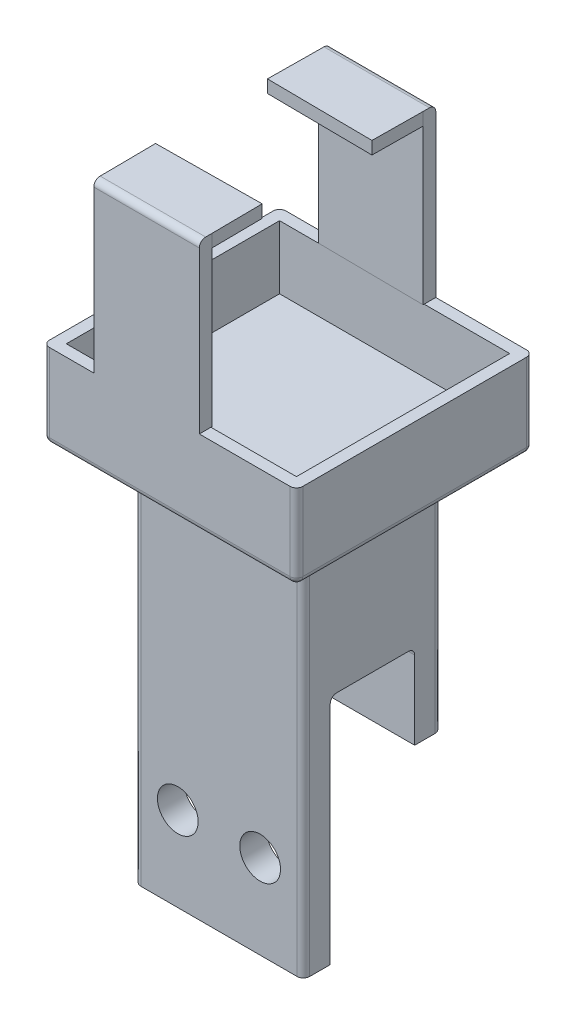
SolidWorks part; units mm, degrees
ref_plane "Front Plane" through (0, 0, 0) normal (0, 0, 1) x (1, 0, 0)
ref_plane "Top Plane" through (0, 0, 0) normal (0, 1, 0) x (1, 0, 0)
ref_plane "Right Plane" through (0, 0, 0) normal (1, 0, 0) x (0, 0, -1)
sketch "Sketch1" plane through (0, 0, 0) normal (1, 0, 0) x (0, 0, -1)
  line L0 (-10, 55) -> (10, 55) construction
  line L1 (-10, 0) -> (-10, 53.5)
  line L2 (-8.5, 55) -> (8.5, 55)
  line L3 (10, 53.5) -> (10, 35)
  line L6 (-16.35, 0) -> (-16.35, 61.35)
  line L7 (-16.35, 61.35) -> (16.35, 61.35)
  line L8 (16.35, 61.35) -> (16.35, 35)
  line L13 (10, -166.8123) -> (-3.9458, 0.265) construction
  line L14 (10, 35) -> (10, -166.8123) construction
  line L15 (16.35, -319.2285) -> (-10.2738, -0.2632) construction
  line L16 (16.35, 35) -> (16.35, -319.2285) construction
  line L17 (10, 35) -> (16.35, 35)
  line L18 (10, 55) -> (10, 35) construction
  line L19 (-10, 0) -> (-10, 55) construction
  line L20 (0, 55) -> (0, -55) construction
  line L21 (-16.35, 0) -> (-10, 0)
  arc A0 (8.5, 55) -> (10, 53.5) centre (8.5, 53.5) cw
  arc A1 (-10, 53.5) -> (-8.5, 55) centre (-8.5, 53.5) cw
  point P17 (10, 55)
  dimension "D5" = 1.5
  dimension "D2" = 20
  dimension "D1" = 6.35
  dimension "D3" = 61.35
  dimension "D4" = 20
  dimension "D6" = 61.35
extrude "Boss-Extrude1" add sketch "Sketch1" along normal blind 40
sketch "Sketch2" plane through (0, 0, 16.35) normal (0, 0, 1) x (1, 0, 0)
  line L0 (0, 20) -> (40, 20) construction
  line L1 (0, 61.35) -> (0, 0) construction
  line L2 (40, 61.35) -> (40, 0) construction
  line L3 (20, 0) -> (20, 61.35) construction
  line L4 (40, 0) -> (0, 0) construction
  line L5 (40, 61.35) -> (0, 61.35) construction
  circle A0 centre (10.25, 20) radius 4.826
  circle A1 centre (29.75, 20) radius 4.826
  dimension "D1" = 9.652
  dimension "D2" = 19.5
  dimension "D3" = 20
extrude "Cut-Extrude2" cut sketch "Sketch2" against normal through all
sketch "Sketch6" plane through (0, 61.35, 0) normal (0, 1, 0) x (1, 0, 0)
  line L0 (0, 0) -> (40, 0) construction
  line L1 (40, 16.35) -> (40, -16.35) construction
  line L2 (20, 16.35) -> (20, -16.35) construction
  line L3 (40, 16.35) -> (0, 16.35) construction
  line L4 (40, -16.35) -> (0, -16.35) construction
  line L10 (0, 16.35) -> (40, 16.35)
  line L11 (0, 16.35) -> (0, -16.35)
  line L20 (40, 16.35) -> (40, -16.35)
  line L21 (0, -16.35) -> (40, -16.35)
extrude "Boss-Extrude2" add sketch "Sketch6" along normal blind 30
sketch "Sketch7" plane through (0, 0, 0) normal (0, 1, 0) x (1, 0, 0)
  line L3 (-10, 28) -> (50, 28)
  line L8 (-10, 28) -> (-10, -28)
  line L9 (-10, -28) -> (50, -28)
  line L10 (50, 28) -> (50, -28)
  line L11 (-10, 28) -> (50, -28) construction
  line L12 (-10, -28) -> (50, 28) construction
  point P0 (20, 0)
  point P6 (20, 0)
  dimension "D1" = 56
  dimension "D2" = 60
extrude "Boss-Extrude3" add sketch "Sketch7" along normal blind 20 from surface at 91.35 starting at face at (20, 91.35, 0)
sketch "Sketch8" plane through (0, 111.35, 0) normal (0, 1, 0) x (1, 0, 0)
  line L0 (20, -28) -> (20, 28) construction
  line L1 (50, -28) -> (-10, -28) construction
  line L2 (-10, 28) -> (50, 28) construction
  line L7 (-7.25, 25.25) -> (47.25, 25.25)
  line L8 (-7.25, 25.25) -> (-7.25, -25.25)
  line L9 (-7.25, -25.25) -> (47.25, -25.25)
  line L10 (47.25, 25.25) -> (47.25, -25.25)
  line L11 (-7.25, 25.25) -> (47.25, -25.25) construction
  line L12 (-7.25, -25.25) -> (47.25, 25.25) construction
  point P12 (20, 0)
  dimension "D1" = 54.5
  dimension "D2" = 50.5
extrude "Cut-Extrude3" cut sketch "Sketch8" against normal blind 15
sketch "Sketch9" plane through (0, 111.35, 0) normal (0, 1, 0) x (1, 0, 0)
  line L1 (2, -25.25) -> (27, -25)
  line L3 (27, -25) -> (27, -28)
  line L4 (-7.25, -25.25) -> (47.25, -25.25) construction
  line L8 (2, -25.25) -> (2, -28)
  line L9 (50, -28) -> (-10, -28) construction
  line L10 (2, -28) -> (27, -28)
extrude "Boss-Extrude4" add sketch "Sketch9" along normal blind 39.65
sketch "Sketch10" plane through (3.9999, 0, 25.23) normal (0.01, 0, 1) x (1, 0, -0.01)
  line L8 (23.0012, 151) -> (-2, 151)
  line L9 (23.0012, 151) -> (23.0012, 148)
  line L10 (-2, 151) -> (-2, 148)
  line L11 (23.0012, 148) -> (-2, 148)
  dimension "D1" = 3
extrude "Boss-Extrude5" add sketch "Sketch10" against normal blind 12
mirror "Mirror1" about plane through (0, 0, 0) normal (0, 0, 1) of "Boss-Extrude4", "Boss-Extrude5"
fillet "Fillet1" radius 1.5 2 edges at (14.5, 151, -28) (14.5, 151, 28)
fillet "Fillet2" radius 1.5 8 edges at (0, 45.675, 16.35) (40, 45.675, 16.35) (40, 63.175, -16.35) (0, 63.175, -16.35) (-10, 101.35, 28) (-10, 101.35, -28) (50, 101.35, -28) (50, 101.35, 28)
fillet "Fillet3" radius 1.5 8 edges at (49.5607, 91.35, 27.5607) (50, 91.35, 0) (49.5607, 91.35, -27.5607) (20, 91.35, -28) (-9.5607, 91.35, -27.5607) (-10, 91.35, 0) (-9.5607, 91.35, 27.5607) (20, 91.35, 28)
